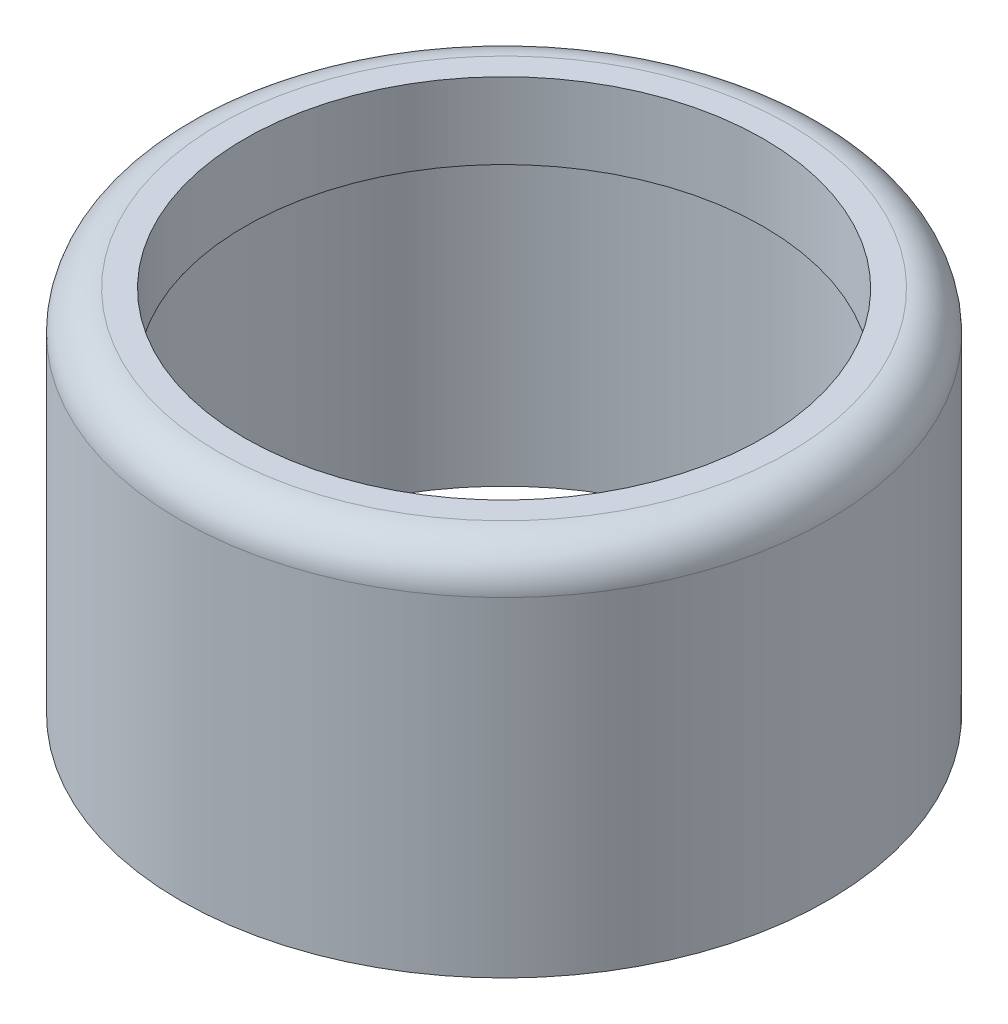
SolidWorks part; units mm, degrees
ref_plane "Front Plane" through (0, 0, 0) normal (0, 0, 1) x (1, 0, 0)
ref_plane "Top Plane" through (0, 0, 0) normal (0, 1, 0) x (1, 0, 0)
ref_plane "Right Plane" through (0, 0, 0) normal (1, 0, 0) x (0, 0, -1)
sketch "Sketch1" plane through (0, 0, 0) normal (0, 0, 1) x (1, 0, 0)
  line L0 (0, 0) -> (0, -42.3795) construction
  line L1 (14.3, -19.8624) -> (14.3, -4.8624)
  line L2 (14.3, -4.8624) -> (13.3, -4.8624)
  line L3 (13.3, -4.8624) -> (13.3, -0.9624)
  line L4 (13.3, -0.9624) -> (14.6, -0.9624)
  line L5 (16.6, -2.9624) -> (16.6, -19.8624)
  line L6 (16.6, -19.8624) -> (14.3, -19.8624)
  arc A0 (16.6, -2.9624) -> (14.6, -0.9624) centre (14.6, -2.9624) ccw
  point P11 (16.6, -0.9624)
  dimension "D6" = 2
  dimension "D1" = 14.3
  dimension "D2" = 13.3
  dimension "D3" = 15
  dimension "D4" = 18.9
  dimension "D5" = 2.3
revolve "Revolve1" add sketch "Sketch1" angle 360 about L0
